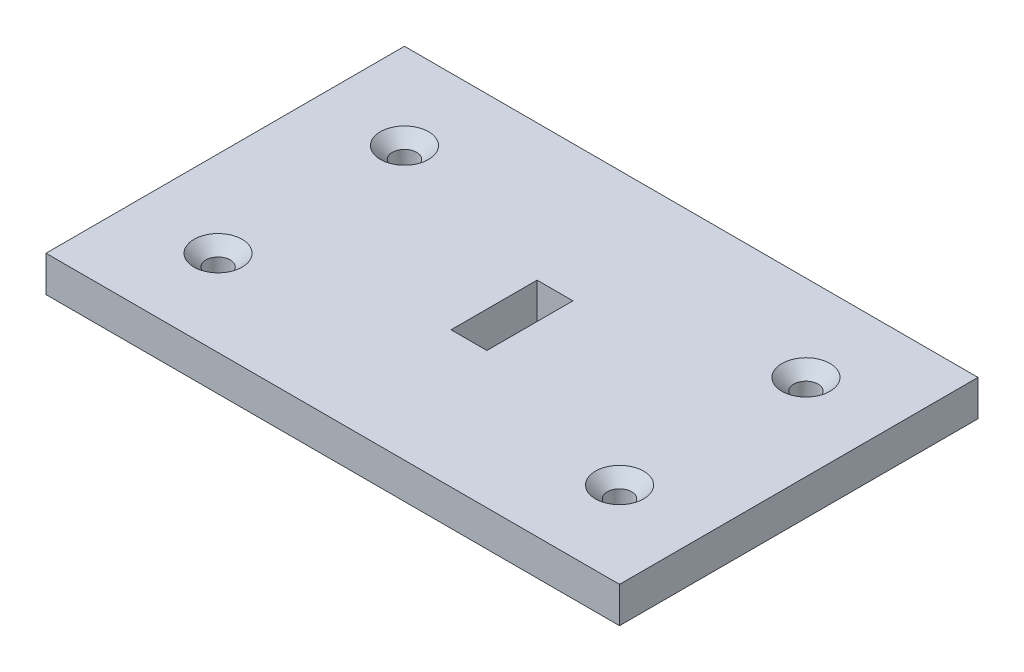
SolidWorks part; units mm, degrees
material "AISI 304"
ref_plane "Front Plane" through (0, 0, 0) normal (0, 0, 1) x (1, 0, 0)
ref_plane "Top Plane" through (0, 0, 0) normal (0, 1, 0) x (1, 0, 0)
ref_plane "Right Plane" through (0, 0, 0) normal (1, 0, 0) x (0, 0, -1)
sketch "Sketch1" plane through (0, 0, 0) normal (0, 1, 0) x (1, 0, 0)
  line L1 (40, -25) -> (-40, -25)
  line L2 (40, -25) -> (40, 25)
  line L3 (40, 25) -> (-40, 25)
  line L4 (-40, -25) -> (-40, 25)
  line L5 (40, -25) -> (-40, 25) construction
  line L6 (40, 25) -> (-40, -25) construction
  point P0 (0, 0)
  dimension "D1" = 80
  dimension "D2" = 50
extrude "Boss-Extrude1" add sketch "Sketch1" along normal mid plane 5 contours L3 L4 L1 L2
sketch "Sketch2" plane through (0, 2.5, 0) normal (0, 1, 0) x (1, 0, 0)
  line L1 (2.5, -6) -> (-2.5, -6)
  line L2 (2.5, -6) -> (2.5, 6)
  line L3 (2.5, 6) -> (-2.5, 6)
  line L4 (-2.5, -6) -> (-2.5, 6)
  line L5 (2.5, -6) -> (-2.5, 6) construction
  line L6 (2.5, 6) -> (-2.5, -6) construction
  point P0 (0, 0)
  dimension "D1" = 12
  dimension "D2" = 5
extrude "Cut-Extrude1" cut sketch "Sketch2" against normal blind 5
hole_wizard "CSK for M3 Hex Socket Countersunk Cap Screw1" positions "Sketch3" profile "Sketch4" countersink size "M3" standard "ISO" end condition through all
sketch "Sketch3" plane through (0, 2.5, 0) normal (0, 1, 0) x (1, 0, 0)
  line L0 (40, -25) -> (40, 25) construction
  line L1 (40, -25) -> (-40, -25) construction
  line L3 (0, 0) -> (0, -34.0106) construction
  line L6 (0, 0) -> (0, 40.0239) construction
  point P4 (28, -13)
  point P23 (28, 13)
  point P38 (-28, -13)
  point P40 (-28, 13)
  dimension "D1" = 12
  dimension "D2" = 12
sketch "Sketch4" plane through (28, 2.5, 13) normal (1, 0, 0) x (0, 0, 1)
  line L0 (0, 0) -> (0, 5)
  line L1 (0, 5) -> (1.7, 5)
  line L2 (1.7, 5) -> (1.7, 1.66)
  line L3 (1.7, 1.66) -> (3.36, 0)
  line L5 (3.36, 0) -> (0, 0)
  line L6 (-1.7, 1.66) -> (-3.36, 0) construction
  line L11 (0, -6.35) -> (0, 107.95) construction
  dimension "Thru Hole Dia." = 3.4
  dimension "Thru Hole Depth" = 5
  dimension "Near C'Sink Dia." = 6.72
  dimension "Near C'Sink Angle" = 90
